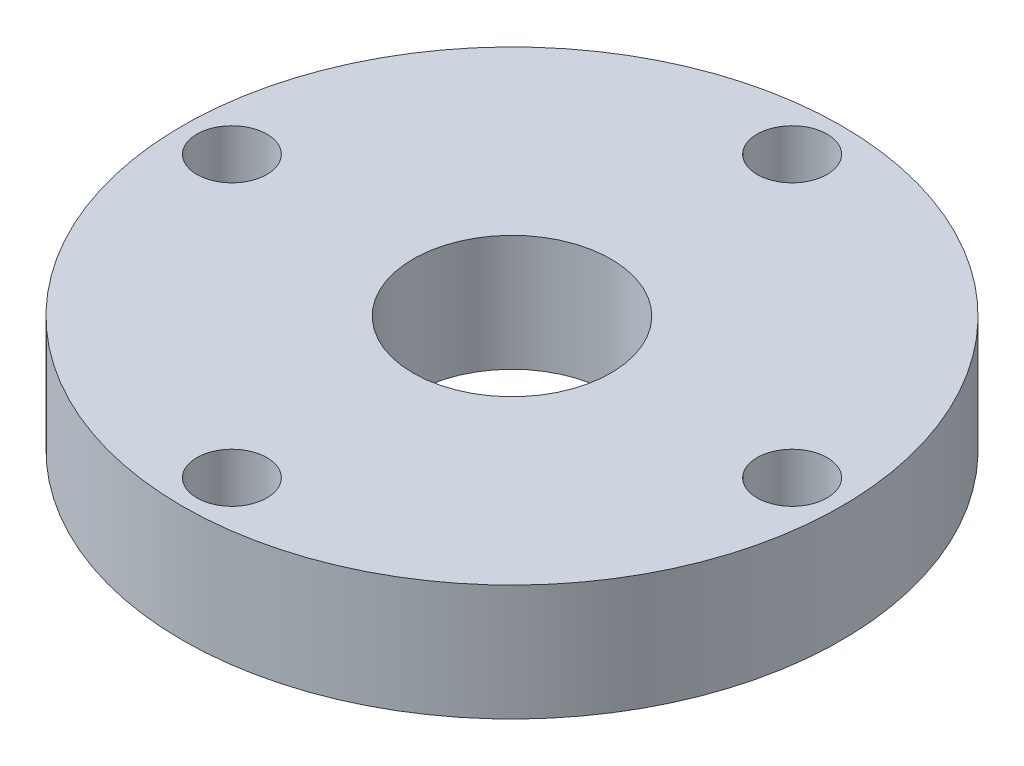
SolidWorks part; units mm, degrees
ref_plane "Front Plane" through (0, 0, 0) normal (1, 0, 0) x (0, 1, 0)
ref_plane "Top Plane" through (0, 0, 0) normal (0, 0, 1) x (0, 1, 0)
ref_plane "Right Plane" through (0, 0, 0) normal (0, 1, 0) x (-1, 0, 0)
sketch "Sketch1" plane through (0, 0, 0) normal (0, 0, 1) x (0, 1, 0)
  line L0 (-11.176, 0) -> (-11.176, 63.5)
  line L1 (-11.176, 63.5) -> (11.176, 63.5)
  line L2 (11.176, 63.5) -> (11.176, 0)
  line L3 (11.176, 0) -> (-11.176, 0)
  line L4 (-36.576, 0) -> (36.576, 0) construction
revolve "Revolve1" add sketch "Sketch1" angle 360 about L4
sketch "Sketch2" plane through (0, 0, 0) normal (0, 1, 0) x (-1, 0, 0)
  circle A0 centre (0, 0) radius 19.05
extrude "Cut-Extrude2" cut sketch "Sketch2" against normal through all from offset 11.176
hole_wizard "CBORE for 5/16 Socket Head Cap Screw1" positions "Sketch4" profile "Sketch3" counterbore size "5/16" standard "ANSI Inch"
sketch "Sketch4" plane through (0, 11.176, 0) normal (0, 1, 0) x (1, 0, 0)
  point P0 (-53.975, 0)
sketch "Sketch3" plane through (-53.975, 11.176, 0) normal (1, 0, 0) x (0, 0, 1)
  line L0 (0, 0) -> (0, 24.977)
  line L1 (0, 24.977) -> (4.3688, 22.352)
  line L2 (4.3688, 22.352) -> (4.3688, 9.652)
  line L3 (4.3688, 9.652) -> (6.7437, 9.652)
  line L4 (6.7437, 9.652) -> (6.7437, 0)
  line L5 (6.7437, 0) -> (0, 0)
  line L10 (0, 24.977) -> (-4.3688, 22.352) construction
  line L11 (0, -6.35) -> (0, 107.95) construction
  dimension "Hole Dia." = 8.7376
  dimension "Hole Depth" = 22.352
  dimension "C'Bore Dia." = 13.4874
  dimension "C'Bore Depth" = 9.652
  dimension "Drill Angle" = 118
hole_wizard "CBORE for 5/16 Socket Head Cap Screw2" positions "Sketch6" profile "Sketch5" counterbore size "5/16" standard "ANSI Inch"
sketch "Sketch6" plane through (0, 11.176, 0) normal (0, 1, 0) x (1, 0, 0)
  point P0 (0, -53.975)
  point P1 (53.975, 0)
  point P3 (0, 53.975)
sketch "Sketch5" plane through (0, 11.176, 53.975) normal (1, 0, 0) x (0, 0, 1)
  line L0 (0, 0) -> (0, 24.977)
  line L1 (0, 24.977) -> (4.3688, 22.352)
  line L2 (4.3688, 22.352) -> (4.3688, 9.652)
  line L3 (4.3688, 9.652) -> (6.7437, 9.652)
  line L4 (6.7437, 9.652) -> (6.7437, 0)
  line L5 (6.7437, 0) -> (0, 0)
  line L10 (0, 24.977) -> (-4.3688, 22.352) construction
  line L11 (0, -6.35) -> (0, 107.95) construction
  dimension "Hole Dia." = 8.7376
  dimension "Hole Depth" = 22.352
  dimension "C'Bore Dia." = 13.4874
  dimension "C'Bore Depth" = 9.652
  dimension "Drill Angle" = 118
